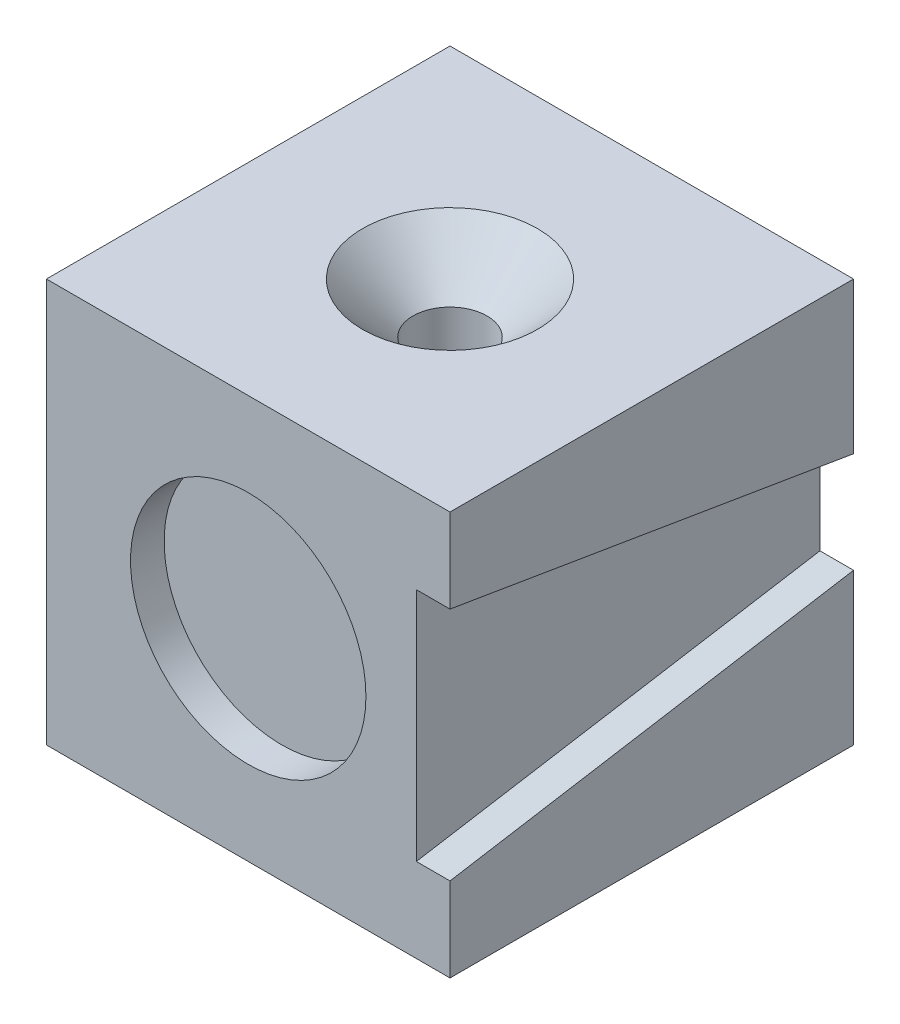
SolidWorks part; units mm, degrees
ref_plane "Front Plane" through (0, 0, 0) normal (0, 0, 1) x (1, 0, 0)
ref_plane "Top Plane" through (0, 0, 0) normal (0, 1, 0) x (1, 0, 0)
ref_plane "Right Plane" through (0, 0, 0) normal (1, 0, 0) x (0, 0, -1)
sketch "Sketch1" plane through (0, 0, 0) normal (0, 1, 0) x (1, 0, 0)
  line L0 (-76.2, 76.2) -> (76.2, -76.2) construction
  line L1 (-76.2, 76.2) -> (76.2, 76.2)
  line L2 (-76.2, 76.2) -> (-76.2, -76.2)
  line L3 (-76.2, -76.2) -> (76.2, -76.2)
  line L4 (76.2, 76.2) -> (76.2, -76.2)
  dimension "D1" = 152.4
extrude "Boss-Extrude1" add sketch "Sketch1" along normal mid plane 152.4
sketch "Sketch2" plane through (0, 0, 0) normal (0, 0, 1) x (1, 0, 0)
  line L0 (0, 0) -> (0, 12.7) construction
  line L1 (0, 12.7) -> (13.97, 12.7)
  line L2 (13.97, 12.7) -> (13.97, 57.15)
  line L3 (13.97, 57.15) -> (33.02, 76.2)
  line L4 (-76.2, 76.2) -> (76.2, 76.2) construction
  line L5 (33.02, 76.2) -> (0, 76.2)
  line L6 (0, 76.2) -> (0, 12.7)
  dimension "D1" = 45
  dimension "D2" = 13.97
  dimension "D3" = 63.5
  dimension "D4" = 19.05
revolve "Cut-Revolve1" cut sketch "Sketch2" angle 360 about L0
sketch "Sketch3" plane through (76.2, 0, 0) normal (1, 0, 0) x (0, 0, -1)
  line L0 (-76.2, 44.45) -> (76.2, 19.05)
  line L1 (-76.2, 76.2) -> (-76.2, -76.2) construction
  line L2 (76.2, 76.2) -> (76.2, -76.2) construction
  line L3 (76.2, 19.05) -> (76.2, -19.05)
  line L4 (76.2, -19.05) -> (-76.2, -44.45)
  line L5 (-76.2, -44.45) -> (-76.2, 44.45)
  line L6 (0, 0) -> (76.2, 0) construction
  line L7 (0, 0) -> (-76.2, 0) construction
  dimension "D1" = 38.1
  dimension "D2" = 88.9
extrude "Cut-Extrude1" cut sketch "Sketch3" against normal blind 12.7
sketch "Sketch4" plane through (0, 0, 76.2) normal (0, 0, 1) x (1, 0, 0)
  circle A0 centre (0, 0) radius 44.45
  dimension "D1" = 88.9
extrude "Cut-Extrude2" cut sketch "Sketch4" against normal blind 12.7
sketch "Sketch5" plane through (0, 0, -76.2) normal (0, 0, -1) x (-1, 0, 0)
  circle A0 centre (0, 0) radius 25.4
  dimension "D1" = 50.8
extrude "Boss-Extrude2" add sketch "Sketch5" along normal blind 25.4
sketch "Sketch6" plane through (-76.2, 0, 0) normal (-1, 0, 0) x (0, 0, 1)
  line L0 (-63.5, 63.5) -> (63.5, -63.5) construction
  line L1 (-63.5, 63.5) -> (63.5, 63.5)
  line L2 (-63.5, 63.5) -> (-63.5, -63.5)
  line L3 (-63.5, -63.5) -> (63.5, -63.5)
  line L4 (63.5, 63.5) -> (63.5, -63.5)
  line L5 (-76.2, 76.2) -> (76.2, 76.2) construction
  dimension "D1" = 12.7
extrude "Cut-Extrude3" cut sketch "Sketch6" against normal blind 12.7
sketch "Sketch7" plane through (0, -76.2, 0) normal (0, -1, 0) x (1, 0, 0)
  line L0 (-76.2, -76.2) -> (-76.2, 76.2) construction
  line L1 (76.2, 76.2) -> (76.2, -76.2) construction
  spline S0 degree 3 poles (-76.2, -61.2868) (-0.0517, -67.934) (-103.8501, 17.1254) (115.2758, 108.3008) (-61.9511, -92.2573) (76.2, -17.3631) knots 0 0 0 0 0.3097 0.56018 1 1 1 1
